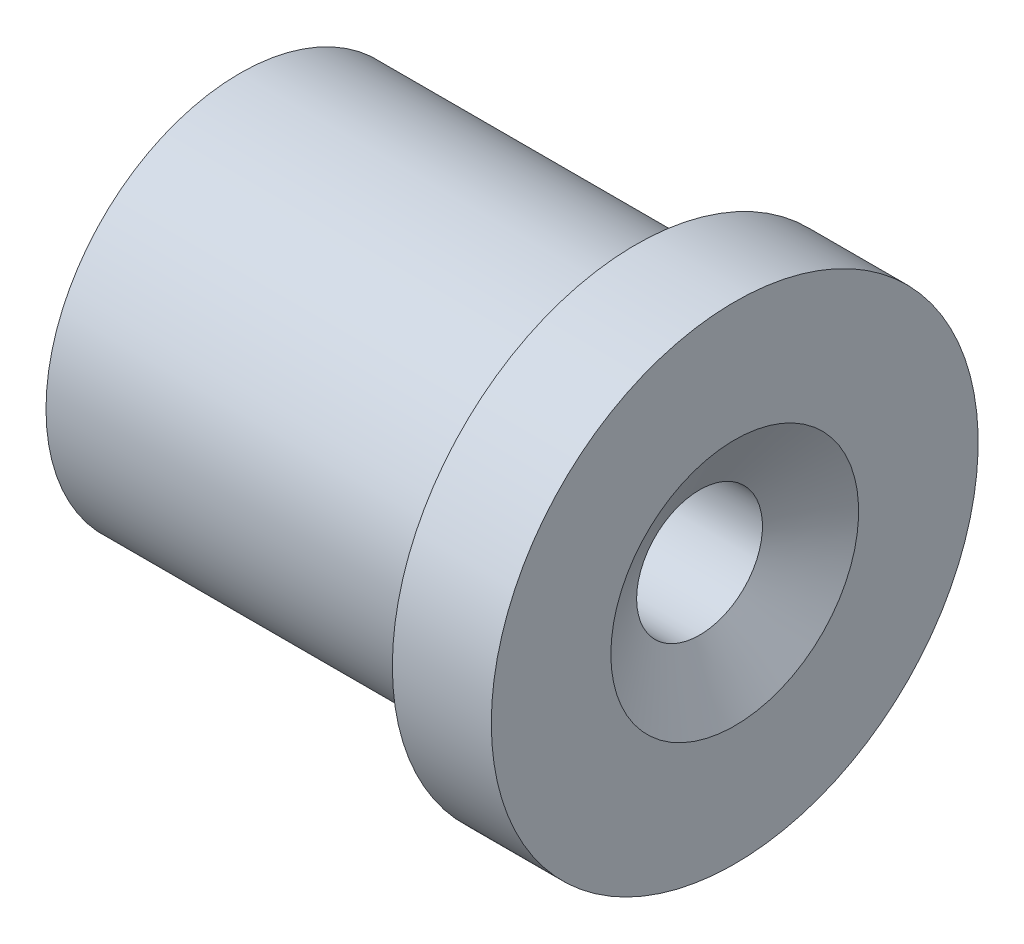
SolidWorks part; units mm, degrees
material "ASTM A36 Steel"
ref_plane "Front Plane" through (0, 0, 0) normal (0, 0, 1) x (1, 0, 0)
ref_plane "Top Plane" through (0, 0, 0) normal (0, 1, 0) x (1, 0, 0)
ref_plane "Right Plane" through (0, 0, 0) normal (1, 0, 0) x (0, 0, -1)
sketch "Sketch2" plane through (0, 0, 0) normal (0, 0, 1) x (1, 0, 0)
  line L0 (16.5963, 0) -> (39.7538, 0) construction
  line L1 (0, 3.9751) -> (0, 7.8105)
  line L2 (-3.175, 6.223) -> (-15.875, 6.223)
  line L3 (-15.875, 6.223) -> (-15.875, 4.572)
  line L4 (-15.875, 4.572) -> (-15.5194, 4.2164)
  line L5 (-5.8689, 2.0193) -> (-1.1292, 2.0193)
  line L6 (-1.1292, 2.0193) -> (0, 3.9751)
  line L7 (-5.8689, 2.0193) -> (-7.1374, 4.2164)
  line L8 (-7.1374, 4.2164) -> (-15.5194, 4.2164)
  line L9 (-3.175, 6.223) -> (-3.175, 7.8105)
  line L10 (-3.175, 7.8105) -> (0, 7.8105)
  dimension "D1" = 60
  dimension "D2" = 45
  dimension "D3" = 4.0386
  dimension "D4" = 12.446
  dimension "D5" = 7.9502
  dimension "D6" = 9.144
  dimension "D7" = 15.875
  dimension "D8" = 8.4328
  dimension "D9" = 60
  dimension "D10" = 8.7376
  dimension "D11" = 3.175
  dimension "D12" = 15.621
revolve "Revolve1" add sketch "Sketch2" angle 360 about L0
